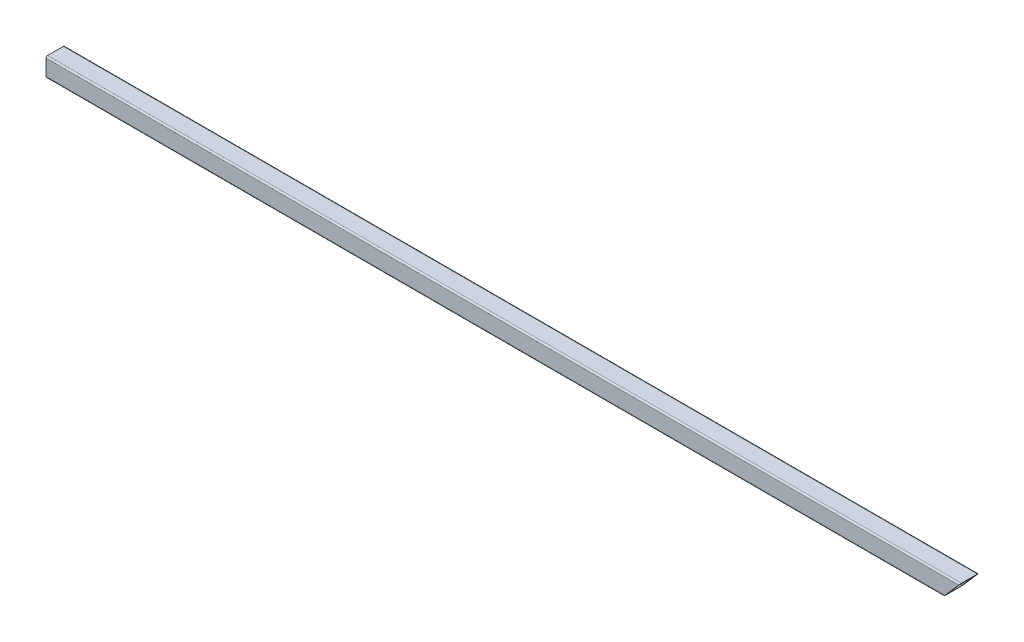
SolidWorks part; units mm, degrees
material "Plain Carbon Steel"
ref_plane "Front Plane" through (0, 0, 0) normal (0, 0, 1) x (1, 0, 0)
ref_plane "Top Plane" through (0, 0, 0) normal (0, 1, 0) x (1, 0, 0)
ref_plane "Right Plane" through (0, 0, 0) normal (1, 0, 0) x (0, 0, -1)
sketch "Sketch1" plane through (0, 0, 0) normal (1, 0, 0) x (0, 0, -1)
  line L0 (0, 2.54) -> (0, 29.21)
  line L1 (-2.54, 31.75) -> (-29.21, 31.75)
  line L2 (-31.75, 29.21) -> (-31.75, 2.54)
  line L3 (-29.21, 0) -> (-2.54, 0)
  line L4 (-4.1275, 4.1275) -> (-4.1275, 27.6225)
  line L5 (-4.1275, 27.6225) -> (-27.6225, 27.6225)
  line L6 (-27.6225, 27.6225) -> (-27.6225, 4.1275)
  line L7 (-27.6225, 4.1275) -> (-4.1275, 4.1275)
  arc A0 (-31.75, 2.54) -> (-29.21, 0) centre (-29.21, 2.54) ccw
  arc A1 (0, 2.54) -> (-2.54, 0) centre (-2.54, 2.54) cw
  arc A2 (0, 29.21) -> (-2.54, 31.75) centre (-2.54, 29.21) ccw
  arc A3 (-31.75, 29.21) -> (-29.21, 31.75) centre (-29.21, 29.21) cw
  arc A4 (-4.1275, 27.6225) -> (-4.1275, 27.6225) centre (-4.1275, 27.6225) ccw
  arc A5 (-27.6225, 27.6225) -> (-27.6225, 27.6225) centre (-27.6225, 27.6225) cw
  arc A6 (-27.6225, 4.1275) -> (-27.6225, 4.1275) centre (-27.6225, 4.1275) ccw
  arc A7 (-4.1275, 4.1275) -> (-4.1275, 4.1275) centre (-4.1275, 4.1275) cw
  point P12 (0, 0)
  point P15 (0, 31.75)
  point P18 (-31.75, 31.75)
  dimension "D3" = 2.54
  dimension "D1" = 31.75
  dimension "D2" = 31.75
  dimension "D4" = 4.1275
extrude "Boss-Extrude1" add sketch "Sketch1" along normal blind 1320.8
scale "Scale4" bodies to scale 101 scale about centroid uniform scaling no x scale factor 1 y scale factor 0.4 z scale factor 0.4
sketch "Sketch4" plane through (0, 0, 9.525) normal (0, 0, 1) x (1, 0, 0)
  line L0 (1311.5819, 15.875) -> (894.3272, 15.875) construction
  line L1 (1320.8, 21.209) -> (670.0204, 21.209) construction
  line L2 (1320.8, 10.541) -> (669.1796, 10.541) construction
sketch "Sketch8" plane through (0, 0, 22.225) normal (0, 0, 1) x (1, 0, 0)
  line L0 (616.5116, 22.225) -> (605.4768, 9.525)
  line L1 (1320.8, 22.225) -> (0, 22.225) construction
  line L2 (439.265, -181.7682) -> (652.686, 63.8582) construction
  line L3 (1320.8, 9.525) -> (0, 9.525) construction
  line L4 (605.4768, 9.525) -> (644.1921, 9.525)
  line L5 (644.1921, 9.525) -> (655.227, 22.225)
  line L6 (655.227, 22.225) -> (616.5116, 22.225)
extrude "Cut-Extrude2" cut sketch "Sketch8" against normal through all
